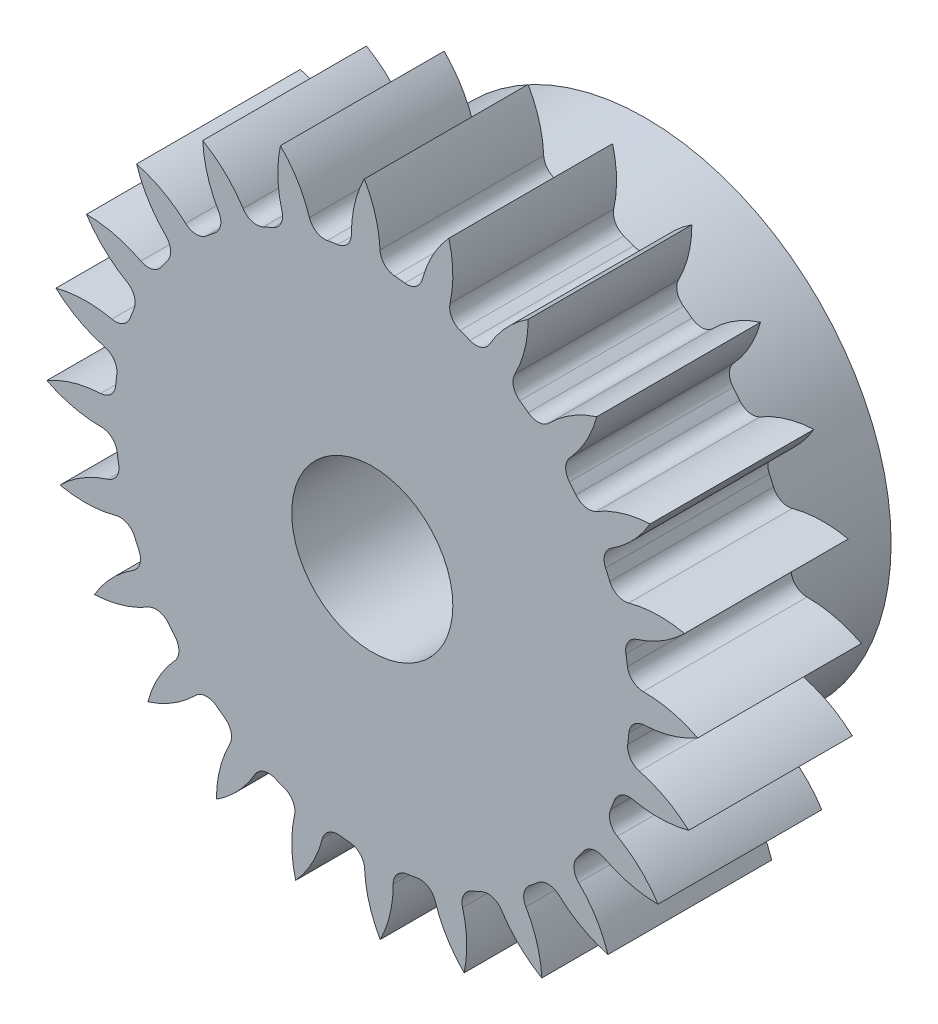
SolidWorks part; units mm, degrees
ref_plane "Front" through (0, 0, 0) normal (0, 0, 1) x (1, 0, 0)
ref_plane "Top" through (0, 0, 0) normal (0, 1, 0) x (1, 0, 0)
ref_plane "Right" through (0, 0, 0) normal (1, 0, 0) x (0, 0, -1)
sketch "Sketch3" plane through (0, 0, 0) normal (0, 0, 1) x (1, 0, 0)
  circle A0 centre (0, 0) radius 55
  dimension "od" = 110
extrude "gearBody" add sketch "Sketch3" along normal blind 25.4
sketch "Sketch2" plane through (0, 0, 0) normal (0, 0, 1) x (1, 0, 0)
  line L0 (0, 0) -> (41.3463, 17.1262) construction
  line L1 (53.7815, -18.596) -> (0, 0) construction
  line L2 (0, 0) -> (36.3143, 0) construction
  line L3 (47.6249, -0.1075) -> (46.5686, -9.9754) construction
  line L5 (47.0967, -5.0414) -> (0, 0) construction
  line L7 (0, 0) -> (44.7529, 0) construction
  arc A0 (44.7438, -0.8982) -> (43.9202, -8.5928) centre (0, 0) ccw construction
  arc A1 (53.8477, 3.7048) -> (51.8435, -15.0184) centre (0, 0) ccw construction
  arc A2 (47.6249, -0.1075) -> (46.5686, -9.9754) centre (0, 0) ccw construction
  arc A3 (39.6333, -5.054) -> (39.805, -3.4494) centre (0, 0) ccw
  arc A4 (53.7815, -18.596) -> (41.4526, -7.7518) centre (36.7845, -25.4896) ccw
  arc A5 (53.7815, -18.596) -> (56.499, 6.7911) centre (0, 0) ccw
  arc A6 (56.499, 6.7911) -> (42.1541, -1.1978) centre (41.3463, 17.1262) cw
  arc A7 (39.805, -3.4494) -> (42.1541, -1.1978) centre (42.2628, -3.6624) cw
  arc A8 (41.4526, -7.7518) -> (39.6333, -5.054) centre (42.0804, -5.3661) cw
  point P6 (56.499, 6.7911)
  point P22 (53.7815, -18.596)
  dimension "baseDia" = 89.5057
  dimension "od" = 107.95
  dimension "pd" = 95.25
  dimension "rd" = 79.9084
  dimension "rFillet" = 2.467
  dimension "pointX" = 56.499
  dimension "pointY" = 6.7911
  dimension "CTT" = 9.8679
  dimension "flankCenterAngle" = 22.5
extrude "toothCut" cut sketch "Sketch2" along normal through all
pattern_circular "CirPattern1" count 24 over 360 about axis through (0, 0, 0) along (0, 0, 1) of "toothCut"
sketch "hub1Dia" plane through (0, 0, 0) normal (0, 0, -1) x (-1, 0, 0)
  circle A0 centre (0, 0) radius 38.1
  dimension "hub1Dia" = 76.2
extrude "hub1" add sketch "hub1Dia" along normal blind 17
sketch "hub2Dia" plane through (0, 0, 25.4) normal (0, 0, 1) x (1, 0, 0)
  circle A0 centre (0, 0) radius 0.5
  dimension "hub2dia" = 1
sketch "boreDia" plane through (0, 0, 0) normal (0, 0, 1) x (1, 0, 0)
  circle A0 centre (0, 0) radius 12.5
  dimension "boreDia" = 25
extrude "bore" cut sketch "boreDia" against normal mid plane 25400
